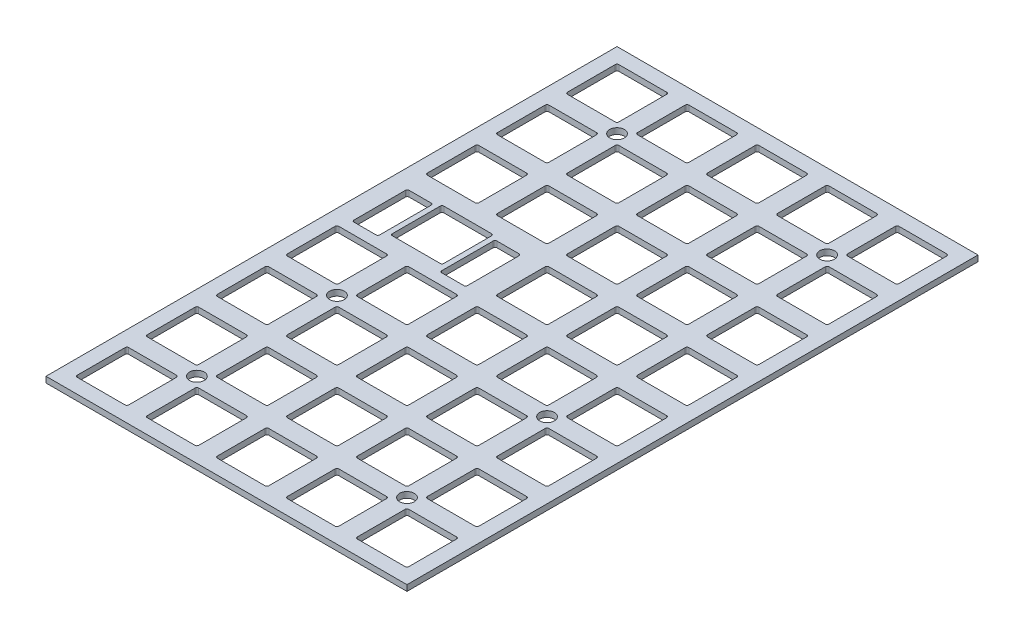
SolidWorks part; units mm, degrees
ref_plane "Front Plane" through (0, 0, 0) normal (0, 0, 1) x (1, 0, 0)
ref_plane "Top Plane" through (0, 0, 0) normal (0, 1, 0) x (1, 0, 0)
ref_plane "Right Plane" through (0, 0, 0) normal (1, 0, 0) x (0, 0, -1)
sketch "Sketch3" plane through (0, 0, 0) normal (0, 1, 0) x (1, 0, 0)
  line L0 (-104.5, -7) -> (-91.5, -7)
  line L1 (-91, -6.5) -> (-91, 6.5)
  line L2 (-91.5, 7) -> (-104.5, 7)
  line L3 (-105, 6.5) -> (-105, -6.5)
  line L4 (-85.45, -7) -> (-72.45, -7)
  line L5 (-71.95, -6.5) -> (-71.95, 6.5)
  line L6 (-72.45, 7) -> (-85.45, 7)
  line L7 (-85.95, 6.5) -> (-85.95, -6.5)
  line L8 (-66.4, -7) -> (-53.4, -7)
  line L9 (-52.9, -6.5) -> (-52.9, 6.5)
  line L10 (-53.4, 7) -> (-66.4, 7)
  line L11 (-66.9, 6.5) -> (-66.9, -6.5)
  line L12 (-47.35, -7) -> (-34.35, -7)
  line L13 (-33.85, -6.5) -> (-33.85, 6.5)
  line L14 (-34.35, 7) -> (-47.35, 7)
  line L15 (-47.85, 6.5) -> (-47.85, -6.5)
  line L16 (-28.3, -7) -> (-15.3, -7)
  line L17 (-14.8, -6.5) -> (-14.8, 6.5)
  line L18 (-15.3, 7) -> (-28.3, 7)
  line L19 (-28.8, 6.5) -> (-28.8, -6.5)
  line L20 (-104.5, -26.05) -> (-91.5, -26.05)
  line L21 (-91, -25.55) -> (-91, -12.55)
  line L22 (-91.5, -12.05) -> (-104.5, -12.05)
  line L23 (-105, -12.55) -> (-105, -25.55)
  line L24 (-85.45, -26.05) -> (-72.45, -26.05)
  line L25 (-71.95, -25.55) -> (-71.95, -12.55)
  line L26 (-72.45, -12.05) -> (-85.45, -12.05)
  line L27 (-85.95, -12.55) -> (-85.95, -25.55)
  line L28 (-66.4, -26.05) -> (-53.4, -26.05)
  line L29 (-52.9, -25.55) -> (-52.9, -12.55)
  line L30 (-53.4, -12.05) -> (-66.4, -12.05)
  line L31 (-66.9, -12.55) -> (-66.9, -25.55)
  line L32 (-47.35, -26.05) -> (-34.35, -26.05)
  line L33 (-33.85, -25.55) -> (-33.85, -12.55)
  line L34 (-34.35, -12.05) -> (-47.35, -12.05)
  line L35 (-47.85, -12.55) -> (-47.85, -25.55)
  line L36 (-28.3, -26.05) -> (-15.3, -26.05)
  line L37 (-14.8, -25.55) -> (-14.8, -12.55)
  line L38 (-15.3, -12.05) -> (-28.3, -12.05)
  line L39 (-28.8, -12.55) -> (-28.8, -25.55)
  line L40 (-104.5, -45.1) -> (-91.5, -45.1)
  line L41 (-91, -44.6) -> (-91, -31.6)
  line L42 (-91.5, -31.1) -> (-104.5, -31.1)
  line L43 (-105, -31.6) -> (-105, -44.6)
  line L44 (-85.45, -45.1) -> (-72.45, -45.1)
  line L45 (-71.95, -44.6) -> (-71.95, -31.6)
  line L46 (-72.45, -31.1) -> (-85.45, -31.1)
  line L47 (-85.95, -31.6) -> (-85.95, -44.6)
  line L48 (-66.4, -45.1) -> (-53.4, -45.1)
  line L49 (-52.9, -44.6) -> (-52.9, -31.6)
  line L50 (-53.4, -31.1) -> (-66.4, -31.1)
  line L51 (-66.9, -31.6) -> (-66.9, -44.6)
  line L52 (-47.35, -45.1) -> (-34.35, -45.1)
  line L53 (-33.85, -44.6) -> (-33.85, -31.6)
  line L54 (-34.35, -31.1) -> (-47.35, -31.1)
  line L55 (-47.85, -31.6) -> (-47.85, -44.6)
  line L56 (-28.3, -45.1) -> (-15.3, -45.1)
  line L57 (-14.8, -44.6) -> (-14.8, -31.6)
  line L58 (-15.3, -31.1) -> (-28.3, -31.1)
  line L59 (-28.8, -31.6) -> (-28.8, -44.6)
  line L60 (-94.975, -64.15) -> (-81.975, -64.15)
  line L61 (-81.475, -63.65) -> (-81.475, -50.65)
  line L62 (-81.975, -50.15) -> (-94.975, -50.15)
  line L63 (-95.475, -50.65) -> (-95.475, -63.65)
  line L64 (-66.4, -64.15) -> (-53.4, -64.15)
  line L65 (-52.9, -63.65) -> (-52.9, -50.65)
  line L66 (-53.4, -50.15) -> (-66.4, -50.15)
  line L67 (-66.9, -50.65) -> (-66.9, -63.65)
  line L68 (-47.35, -64.15) -> (-34.35, -64.15)
  line L69 (-33.85, -63.65) -> (-33.85, -50.65)
  line L70 (-34.35, -50.15) -> (-47.35, -50.15)
  line L71 (-47.85, -50.65) -> (-47.85, -63.65)
  line L72 (-28.3, -64.15) -> (-15.3, -64.15)
  line L73 (-14.8, -63.65) -> (-14.8, -50.65)
  line L74 (-15.3, -50.15) -> (-28.3, -50.15)
  line L75 (-28.8, -50.65) -> (-28.8, -63.65)
  line L76 (-104.5, -83.2) -> (-91.5, -83.2)
  line L77 (-91, -82.7) -> (-91, -69.7)
  line L78 (-91.5, -69.2) -> (-104.5, -69.2)
  line L79 (-105, -69.7) -> (-105, -82.7)
  line L80 (-85.45, -83.2) -> (-72.45, -83.2)
  line L81 (-71.95, -82.7) -> (-71.95, -69.7)
  line L82 (-72.45, -69.2) -> (-85.45, -69.2)
  line L83 (-85.95, -69.7) -> (-85.95, -82.7)
  line L84 (-66.4, -83.2) -> (-53.4, -83.2)
  line L85 (-52.9, -82.7) -> (-52.9, -69.7)
  line L86 (-53.4, -69.2) -> (-66.4, -69.2)
  line L87 (-66.9, -69.7) -> (-66.9, -82.7)
  line L88 (-47.35, -83.2) -> (-34.35, -83.2)
  line L89 (-33.85, -82.7) -> (-33.85, -69.7)
  line L90 (-34.35, -69.2) -> (-47.35, -69.2)
  line L91 (-47.85, -69.7) -> (-47.85, -82.7)
  line L92 (-28.3, -83.2) -> (-15.3, -83.2)
  line L93 (-14.8, -82.7) -> (-14.8, -69.7)
  line L94 (-15.3, -69.2) -> (-28.3, -69.2)
  line L95 (-28.8, -69.7) -> (-28.8, -82.7)
  line L96 (-104.5, -102.25) -> (-91.5, -102.25)
  line L97 (-91, -101.75) -> (-91, -88.75)
  line L98 (-91.5, -88.25) -> (-104.5, -88.25)
  line L99 (-105, -88.75) -> (-105, -101.75)
  line L100 (-85.45, -102.25) -> (-72.45, -102.25)
  line L101 (-71.95, -101.75) -> (-71.95, -88.75)
  line L102 (-72.45, -88.25) -> (-85.45, -88.25)
  line L103 (-85.95, -88.75) -> (-85.95, -101.75)
  line L104 (-66.4, -102.25) -> (-53.4, -102.25)
  line L105 (-52.9, -101.75) -> (-52.9, -88.75)
  line L106 (-53.4, -88.25) -> (-66.4, -88.25)
  line L107 (-66.9, -88.75) -> (-66.9, -101.75)
  line L108 (-47.35, -102.25) -> (-34.35, -102.25)
  line L109 (-33.85, -101.75) -> (-33.85, -88.75)
  line L110 (-34.35, -88.25) -> (-47.35, -88.25)
  line L111 (-47.85, -88.75) -> (-47.85, -101.75)
  line L112 (-28.3, -102.25) -> (-15.3, -102.25)
  line L113 (-14.8, -101.75) -> (-14.8, -88.75)
  line L114 (-15.3, -88.25) -> (-28.3, -88.25)
  line L115 (-28.8, -88.75) -> (-28.8, -101.75)
  line L116 (-104.5, -121.3) -> (-91.5, -121.3)
  line L117 (-91, -120.8) -> (-91, -107.8)
  line L118 (-91.5, -107.3) -> (-104.5, -107.3)
  line L119 (-105, -107.8) -> (-105, -120.8)
  line L120 (-85.45, -121.3) -> (-72.45, -121.3)
  line L121 (-71.95, -120.8) -> (-71.95, -107.8)
  line L122 (-72.45, -107.3) -> (-85.45, -107.3)
  line L123 (-85.95, -107.8) -> (-85.95, -120.8)
  line L124 (-66.4, -121.3) -> (-53.4, -121.3)
  line L125 (-52.9, -120.8) -> (-52.9, -107.8)
  line L126 (-53.4, -107.3) -> (-66.4, -107.3)
  line L127 (-66.9, -107.8) -> (-66.9, -120.8)
  line L128 (-47.35, -121.3) -> (-34.35, -121.3)
  line L129 (-33.85, -120.8) -> (-33.85, -107.8)
  line L130 (-34.35, -107.3) -> (-47.35, -107.3)
  line L131 (-47.85, -107.8) -> (-47.85, -120.8)
  line L132 (-28.3, -121.3) -> (-15.3, -121.3)
  line L133 (-14.8, -120.8) -> (-14.8, -107.8)
  line L134 (-15.3, -107.3) -> (-28.3, -107.3)
  line L135 (-28.8, -107.8) -> (-28.8, -120.8)
  line L136 (-104.5, -140.35) -> (-91.5, -140.35)
  line L137 (-91, -139.85) -> (-91, -126.85)
  line L138 (-91.5, -126.35) -> (-104.5, -126.35)
  line L139 (-105, -126.85) -> (-105, -139.85)
  line L140 (-85.45, -140.35) -> (-72.45, -140.35)
  line L141 (-71.95, -139.85) -> (-71.95, -126.85)
  line L142 (-72.45, -126.35) -> (-85.45, -126.35)
  line L143 (-85.95, -126.85) -> (-85.95, -139.85)
  line L144 (-66.4, -140.35) -> (-53.4, -140.35)
  line L145 (-52.9, -139.85) -> (-52.9, -126.85)
  line L146 (-53.4, -126.35) -> (-66.4, -126.35)
  line L147 (-66.9, -126.85) -> (-66.9, -139.85)
  line L148 (-47.35, -140.35) -> (-34.35, -140.35)
  line L149 (-33.85, -139.85) -> (-33.85, -126.85)
  line L150 (-34.35, -126.35) -> (-47.35, -126.35)
  line L151 (-47.85, -126.85) -> (-47.85, -139.85)
  line L152 (-28.3, -140.35) -> (-15.3, -140.35)
  line L153 (-14.8, -139.85) -> (-14.8, -126.85)
  line L154 (-15.3, -126.35) -> (-28.3, -126.35)
  line L155 (-28.8, -126.85) -> (-28.8, -139.85)
  line L156 (-103.413, -66.15) -> (-97.413, -66.15)
  line L157 (-96.913, -65.65) -> (-96.913, -51.65)
  line L158 (-97.413, -51.15) -> (-103.413, -51.15)
  line L159 (-103.913, -51.65) -> (-103.913, -65.65)
  line L160 (-79.537, -66.15) -> (-73.537, -66.15)
  line L161 (-73.037, -65.65) -> (-73.037, -51.65)
  line L162 (-73.537, -51.15) -> (-79.537, -51.15)
  line L163 (-80.037, -51.65) -> (-80.037, -65.65)
  line L165 (-109, 11) -> (-10.8, 11)
  line L166 (-109, 11) -> (-109, -144.35)
  line L167 (-109, -144.35) -> (-10.8, -144.35)
  line L168 (-10.8, 11) -> (-10.8, -144.35)
  arc A0 (-105, -6.5) -> (-104.5, -7) centre (-104.5, -6.5) ccw
  arc A1 (-91.5, -7) -> (-91, -6.5) centre (-91.5, -6.5) ccw
  arc A2 (-91, 6.5) -> (-91.5, 7) centre (-91.5, 6.5) ccw
  arc A3 (-104.5, 7) -> (-105, 6.5) centre (-104.5, 6.5) ccw
  arc A4 (-85.95, -6.5) -> (-85.45, -7) centre (-85.45, -6.5) ccw
  arc A5 (-72.45, -7) -> (-71.95, -6.5) centre (-72.45, -6.5) ccw
  arc A6 (-71.95, 6.5) -> (-72.45, 7) centre (-72.45, 6.5) ccw
  arc A7 (-85.45, 7) -> (-85.95, 6.5) centre (-85.45, 6.5) ccw
  arc A8 (-66.9, -6.5) -> (-66.4, -7) centre (-66.4, -6.5) ccw
  arc A9 (-53.4, -7) -> (-52.9, -6.5) centre (-53.4, -6.5) ccw
  arc A10 (-52.9, 6.5) -> (-53.4, 7) centre (-53.4, 6.5) ccw
  arc A11 (-66.4, 7) -> (-66.9, 6.5) centre (-66.4, 6.5) ccw
  arc A12 (-47.85, -6.5) -> (-47.35, -7) centre (-47.35, -6.5) ccw
  arc A13 (-34.35, -7) -> (-33.85, -6.5) centre (-34.35, -6.5) ccw
  arc A14 (-33.85, 6.5) -> (-34.35, 7) centre (-34.35, 6.5) ccw
  arc A15 (-47.35, 7) -> (-47.85, 6.5) centre (-47.35, 6.5) ccw
  arc A16 (-28.8, -6.5) -> (-28.3, -7) centre (-28.3, -6.5) ccw
  arc A17 (-15.3, -7) -> (-14.8, -6.5) centre (-15.3, -6.5) ccw
  arc A18 (-14.8, 6.5) -> (-15.3, 7) centre (-15.3, 6.5) ccw
  arc A19 (-28.3, 7) -> (-28.8, 6.5) centre (-28.3, 6.5) ccw
  arc A20 (-105, -25.55) -> (-104.5, -26.05) centre (-104.5, -25.55) ccw
  arc A21 (-91.5, -26.05) -> (-91, -25.55) centre (-91.5, -25.55) ccw
  arc A22 (-91, -12.55) -> (-91.5, -12.05) centre (-91.5, -12.55) ccw
  arc A23 (-104.5, -12.05) -> (-105, -12.55) centre (-104.5, -12.55) ccw
  arc A24 (-85.95, -25.55) -> (-85.45, -26.05) centre (-85.45, -25.55) ccw
  arc A25 (-72.45, -26.05) -> (-71.95, -25.55) centre (-72.45, -25.55) ccw
  arc A26 (-71.95, -12.55) -> (-72.45, -12.05) centre (-72.45, -12.55) ccw
  arc A27 (-85.45, -12.05) -> (-85.95, -12.55) centre (-85.45, -12.55) ccw
  arc A28 (-66.9, -25.55) -> (-66.4, -26.05) centre (-66.4, -25.55) ccw
  arc A29 (-53.4, -26.05) -> (-52.9, -25.55) centre (-53.4, -25.55) ccw
  arc A30 (-52.9, -12.55) -> (-53.4, -12.05) centre (-53.4, -12.55) ccw
  arc A31 (-66.4, -12.05) -> (-66.9, -12.55) centre (-66.4, -12.55) ccw
  arc A32 (-47.85, -25.55) -> (-47.35, -26.05) centre (-47.35, -25.55) ccw
  arc A33 (-34.35, -26.05) -> (-33.85, -25.55) centre (-34.35, -25.55) ccw
  arc A34 (-33.85, -12.55) -> (-34.35, -12.05) centre (-34.35, -12.55) ccw
  arc A35 (-47.35, -12.05) -> (-47.85, -12.55) centre (-47.35, -12.55) ccw
  arc A36 (-28.8, -25.55) -> (-28.3, -26.05) centre (-28.3, -25.55) ccw
  arc A37 (-15.3, -26.05) -> (-14.8, -25.55) centre (-15.3, -25.55) ccw
  arc A38 (-14.8, -12.55) -> (-15.3, -12.05) centre (-15.3, -12.55) ccw
  arc A39 (-28.3, -12.05) -> (-28.8, -12.55) centre (-28.3, -12.55) ccw
  arc A40 (-105, -44.6) -> (-104.5, -45.1) centre (-104.5, -44.6) ccw
  arc A41 (-91.5, -45.1) -> (-91, -44.6) centre (-91.5, -44.6) ccw
  arc A42 (-91, -31.6) -> (-91.5, -31.1) centre (-91.5, -31.6) ccw
  arc A43 (-104.5, -31.1) -> (-105, -31.6) centre (-104.5, -31.6) ccw
  arc A44 (-85.95, -44.6) -> (-85.45, -45.1) centre (-85.45, -44.6) ccw
  arc A45 (-72.45, -45.1) -> (-71.95, -44.6) centre (-72.45, -44.6) ccw
  arc A46 (-71.95, -31.6) -> (-72.45, -31.1) centre (-72.45, -31.6) ccw
  arc A47 (-85.45, -31.1) -> (-85.95, -31.6) centre (-85.45, -31.6) ccw
  arc A48 (-66.9, -44.6) -> (-66.4, -45.1) centre (-66.4, -44.6) ccw
  arc A49 (-53.4, -45.1) -> (-52.9, -44.6) centre (-53.4, -44.6) ccw
  arc A50 (-52.9, -31.6) -> (-53.4, -31.1) centre (-53.4, -31.6) ccw
  arc A51 (-66.4, -31.1) -> (-66.9, -31.6) centre (-66.4, -31.6) ccw
  arc A52 (-47.85, -44.6) -> (-47.35, -45.1) centre (-47.35, -44.6) ccw
  arc A53 (-34.35, -45.1) -> (-33.85, -44.6) centre (-34.35, -44.6) ccw
  arc A54 (-33.85, -31.6) -> (-34.35, -31.1) centre (-34.35, -31.6) ccw
  arc A55 (-47.35, -31.1) -> (-47.85, -31.6) centre (-47.35, -31.6) ccw
  arc A56 (-28.8, -44.6) -> (-28.3, -45.1) centre (-28.3, -44.6) ccw
  arc A57 (-15.3, -45.1) -> (-14.8, -44.6) centre (-15.3, -44.6) ccw
  arc A58 (-14.8, -31.6) -> (-15.3, -31.1) centre (-15.3, -31.6) ccw
  arc A59 (-28.3, -31.1) -> (-28.8, -31.6) centre (-28.3, -31.6) ccw
  arc A60 (-95.475, -63.65) -> (-94.975, -64.15) centre (-94.975, -63.65) ccw
  arc A61 (-81.975, -64.15) -> (-81.475, -63.65) centre (-81.975, -63.65) ccw
  arc A62 (-81.475, -50.65) -> (-81.975, -50.15) centre (-81.975, -50.65) ccw
  arc A63 (-94.975, -50.15) -> (-95.475, -50.65) centre (-94.975, -50.65) ccw
  arc A64 (-66.9, -63.65) -> (-66.4, -64.15) centre (-66.4, -63.65) ccw
  arc A65 (-53.4, -64.15) -> (-52.9, -63.65) centre (-53.4, -63.65) ccw
  arc A66 (-52.9, -50.65) -> (-53.4, -50.15) centre (-53.4, -50.65) ccw
  arc A67 (-66.4, -50.15) -> (-66.9, -50.65) centre (-66.4, -50.65) ccw
  arc A68 (-47.85, -63.65) -> (-47.35, -64.15) centre (-47.35, -63.65) ccw
  arc A69 (-34.35, -64.15) -> (-33.85, -63.65) centre (-34.35, -63.65) ccw
  arc A70 (-33.85, -50.65) -> (-34.35, -50.15) centre (-34.35, -50.65) ccw
  arc A71 (-47.35, -50.15) -> (-47.85, -50.65) centre (-47.35, -50.65) ccw
  arc A72 (-28.8, -63.65) -> (-28.3, -64.15) centre (-28.3, -63.65) ccw
  arc A73 (-15.3, -64.15) -> (-14.8, -63.65) centre (-15.3, -63.65) ccw
  arc A74 (-14.8, -50.65) -> (-15.3, -50.15) centre (-15.3, -50.65) ccw
  arc A75 (-28.3, -50.15) -> (-28.8, -50.65) centre (-28.3, -50.65) ccw
  arc A76 (-105, -82.7) -> (-104.5, -83.2) centre (-104.5, -82.7) ccw
  arc A77 (-91.5, -83.2) -> (-91, -82.7) centre (-91.5, -82.7) ccw
  arc A78 (-91, -69.7) -> (-91.5, -69.2) centre (-91.5, -69.7) ccw
  arc A79 (-104.5, -69.2) -> (-105, -69.7) centre (-104.5, -69.7) ccw
  arc A80 (-85.95, -82.7) -> (-85.45, -83.2) centre (-85.45, -82.7) ccw
  arc A81 (-72.45, -83.2) -> (-71.95, -82.7) centre (-72.45, -82.7) ccw
  arc A82 (-71.95, -69.7) -> (-72.45, -69.2) centre (-72.45, -69.7) ccw
  arc A83 (-85.45, -69.2) -> (-85.95, -69.7) centre (-85.45, -69.7) ccw
  arc A84 (-66.9, -82.7) -> (-66.4, -83.2) centre (-66.4, -82.7) ccw
  arc A85 (-53.4, -83.2) -> (-52.9, -82.7) centre (-53.4, -82.7) ccw
  arc A86 (-52.9, -69.7) -> (-53.4, -69.2) centre (-53.4, -69.7) ccw
  arc A87 (-66.4, -69.2) -> (-66.9, -69.7) centre (-66.4, -69.7) ccw
  arc A88 (-47.85, -82.7) -> (-47.35, -83.2) centre (-47.35, -82.7) ccw
  arc A89 (-34.35, -83.2) -> (-33.85, -82.7) centre (-34.35, -82.7) ccw
  arc A90 (-33.85, -69.7) -> (-34.35, -69.2) centre (-34.35, -69.7) ccw
  arc A91 (-47.35, -69.2) -> (-47.85, -69.7) centre (-47.35, -69.7) ccw
  arc A92 (-28.8, -82.7) -> (-28.3, -83.2) centre (-28.3, -82.7) ccw
  arc A93 (-15.3, -83.2) -> (-14.8, -82.7) centre (-15.3, -82.7) ccw
  arc A94 (-14.8, -69.7) -> (-15.3, -69.2) centre (-15.3, -69.7) ccw
  arc A95 (-28.3, -69.2) -> (-28.8, -69.7) centre (-28.3, -69.7) ccw
  arc A96 (-105, -101.75) -> (-104.5, -102.25) centre (-104.5, -101.75) ccw
  arc A97 (-91.5, -102.25) -> (-91, -101.75) centre (-91.5, -101.75) ccw
  arc A98 (-91, -88.75) -> (-91.5, -88.25) centre (-91.5, -88.75) ccw
  arc A99 (-104.5, -88.25) -> (-105, -88.75) centre (-104.5, -88.75) ccw
  arc A100 (-85.95, -101.75) -> (-85.45, -102.25) centre (-85.45, -101.75) ccw
  arc A101 (-72.45, -102.25) -> (-71.95, -101.75) centre (-72.45, -101.75) ccw
  arc A102 (-71.95, -88.75) -> (-72.45, -88.25) centre (-72.45, -88.75) ccw
  arc A103 (-85.45, -88.25) -> (-85.95, -88.75) centre (-85.45, -88.75) ccw
  arc A104 (-66.9, -101.75) -> (-66.4, -102.25) centre (-66.4, -101.75) ccw
  arc A105 (-53.4, -102.25) -> (-52.9, -101.75) centre (-53.4, -101.75) ccw
  arc A106 (-52.9, -88.75) -> (-53.4, -88.25) centre (-53.4, -88.75) ccw
  arc A107 (-66.4, -88.25) -> (-66.9, -88.75) centre (-66.4, -88.75) ccw
  arc A108 (-47.85, -101.75) -> (-47.35, -102.25) centre (-47.35, -101.75) ccw
  arc A109 (-34.35, -102.25) -> (-33.85, -101.75) centre (-34.35, -101.75) ccw
  arc A110 (-33.85, -88.75) -> (-34.35, -88.25) centre (-34.35, -88.75) ccw
  arc A111 (-47.35, -88.25) -> (-47.85, -88.75) centre (-47.35, -88.75) ccw
  arc A112 (-28.8, -101.75) -> (-28.3, -102.25) centre (-28.3, -101.75) ccw
  arc A113 (-15.3, -102.25) -> (-14.8, -101.75) centre (-15.3, -101.75) ccw
  arc A114 (-14.8, -88.75) -> (-15.3, -88.25) centre (-15.3, -88.75) ccw
  arc A115 (-28.3, -88.25) -> (-28.8, -88.75) centre (-28.3, -88.75) ccw
  arc A116 (-105, -120.8) -> (-104.5, -121.3) centre (-104.5, -120.8) ccw
  arc A117 (-91.5, -121.3) -> (-91, -120.8) centre (-91.5, -120.8) ccw
  arc A118 (-91, -107.8) -> (-91.5, -107.3) centre (-91.5, -107.8) ccw
  arc A119 (-104.5, -107.3) -> (-105, -107.8) centre (-104.5, -107.8) ccw
  arc A120 (-85.95, -120.8) -> (-85.45, -121.3) centre (-85.45, -120.8) ccw
  arc A121 (-72.45, -121.3) -> (-71.95, -120.8) centre (-72.45, -120.8) ccw
  arc A122 (-71.95, -107.8) -> (-72.45, -107.3) centre (-72.45, -107.8) ccw
  arc A123 (-85.45, -107.3) -> (-85.95, -107.8) centre (-85.45, -107.8) ccw
  arc A124 (-66.9, -120.8) -> (-66.4, -121.3) centre (-66.4, -120.8) ccw
  arc A125 (-53.4, -121.3) -> (-52.9, -120.8) centre (-53.4, -120.8) ccw
  arc A126 (-52.9, -107.8) -> (-53.4, -107.3) centre (-53.4, -107.8) ccw
  arc A127 (-66.4, -107.3) -> (-66.9, -107.8) centre (-66.4, -107.8) ccw
  arc A128 (-47.85, -120.8) -> (-47.35, -121.3) centre (-47.35, -120.8) ccw
  arc A129 (-34.35, -121.3) -> (-33.85, -120.8) centre (-34.35, -120.8) ccw
  arc A130 (-33.85, -107.8) -> (-34.35, -107.3) centre (-34.35, -107.8) ccw
  arc A131 (-47.35, -107.3) -> (-47.85, -107.8) centre (-47.35, -107.8) ccw
  arc A132 (-28.8, -120.8) -> (-28.3, -121.3) centre (-28.3, -120.8) ccw
  arc A133 (-15.3, -121.3) -> (-14.8, -120.8) centre (-15.3, -120.8) ccw
  arc A134 (-14.8, -107.8) -> (-15.3, -107.3) centre (-15.3, -107.8) ccw
  arc A135 (-28.3, -107.3) -> (-28.8, -107.8) centre (-28.3, -107.8) ccw
  arc A136 (-105, -139.85) -> (-104.5, -140.35) centre (-104.5, -139.85) ccw
  arc A137 (-91.5, -140.35) -> (-91, -139.85) centre (-91.5, -139.85) ccw
  arc A138 (-91, -126.85) -> (-91.5, -126.35) centre (-91.5, -126.85) ccw
  arc A139 (-104.5, -126.35) -> (-105, -126.85) centre (-104.5, -126.85) ccw
  arc A140 (-85.95, -139.85) -> (-85.45, -140.35) centre (-85.45, -139.85) ccw
  arc A141 (-72.45, -140.35) -> (-71.95, -139.85) centre (-72.45, -139.85) ccw
  arc A142 (-71.95, -126.85) -> (-72.45, -126.35) centre (-72.45, -126.85) ccw
  arc A143 (-85.45, -126.35) -> (-85.95, -126.85) centre (-85.45, -126.85) ccw
  arc A144 (-66.9, -139.85) -> (-66.4, -140.35) centre (-66.4, -139.85) ccw
  arc A145 (-53.4, -140.35) -> (-52.9, -139.85) centre (-53.4, -139.85) ccw
  arc A146 (-52.9, -126.85) -> (-53.4, -126.35) centre (-53.4, -126.85) ccw
  arc A147 (-66.4, -126.35) -> (-66.9, -126.85) centre (-66.4, -126.85) ccw
  arc A148 (-47.85, -139.85) -> (-47.35, -140.35) centre (-47.35, -139.85) ccw
  arc A149 (-34.35, -140.35) -> (-33.85, -139.85) centre (-34.35, -139.85) ccw
  arc A150 (-33.85, -126.85) -> (-34.35, -126.35) centre (-34.35, -126.85) ccw
  arc A151 (-47.35, -126.35) -> (-47.85, -126.85) centre (-47.35, -126.85) ccw
  arc A152 (-28.8, -139.85) -> (-28.3, -140.35) centre (-28.3, -139.85) ccw
  arc A153 (-15.3, -140.35) -> (-14.8, -139.85) centre (-15.3, -139.85) ccw
  arc A154 (-14.8, -126.85) -> (-15.3, -126.35) centre (-15.3, -126.85) ccw
  arc A155 (-28.3, -126.35) -> (-28.8, -126.85) centre (-28.3, -126.85) ccw
  arc A156 (-103.913, -65.65) -> (-103.413, -66.15) centre (-103.413, -65.65) ccw
  arc A157 (-97.413, -66.15) -> (-96.913, -65.65) centre (-97.413, -65.65) ccw
  arc A158 (-96.913, -51.65) -> (-97.413, -51.15) centre (-97.413, -51.65) ccw
  arc A159 (-103.413, -51.15) -> (-103.913, -51.65) centre (-103.413, -51.65) ccw
  arc A160 (-80.037, -65.65) -> (-79.537, -66.15) centre (-79.537, -65.65) ccw
  arc A161 (-73.537, -66.15) -> (-73.037, -65.65) centre (-73.537, -65.65) ccw
  arc A162 (-73.037, -51.65) -> (-73.537, -51.15) centre (-73.537, -51.65) ccw
  arc A163 (-79.537, -51.15) -> (-80.037, -51.65) centre (-79.537, -51.65) ccw
  dimension "D1" = 4
  dimension "D2" = 4
  dimension "D3" = 4
  dimension "D4" = 4
  dimension "D5" = 98.2
extrude "Boss-Extrude2" add sketch "Sketch3" along normal blind 1.6 separate body
sketch "Sketch4" plane through (0, 1.6, 0) normal (0, 1, 0) x (1, 0, 0)
  line L0 (-10.8, -144.35) -> (-10.8, 11) construction
  line L1 (-104.5, -7) -> (-104.5, -12.05) construction
  line L2 (-104.5, -83.2) -> (-104.5, -88.25) construction
  line L3 (-104.5, -121.3) -> (-104.5, -126.35) construction
  line L4 (-91, 6.5) -> (-85.95, 6.5) construction
  line L5 (-33.85, 6.5) -> (-28.8, 6.5) construction
  circle A0 centre (-88.475, -9.525) radius 2
  circle A1 centre (-31.325, -9.525) radius 2
  circle A2 centre (-88.475, -85.725) radius 2
  circle A3 centre (-31.325, -85.725) radius 2
  circle A4 centre (-88.475, -123.825) radius 2
  circle A5 centre (-31.325, -123.825) radius 2
  point P28 (-104.5, -123.825)
  point P29 (-104.5, -85.725)
  point P30 (-104.5, -9.525)
  point P39 (-31.325, 6.5)
  point P40 (-88.475, 6.5)
  point P41 (0, 0)
  point P42 (0, 0)
  point P43 (0, 0)
  point P44 (0, 0)
  point P45 (0, 0)
  point P46 (0, 0)
  point P47 (0, 0)
  dimension "D2" = 4
  dimension "D1" = 98.2
extrude "Cut-Extrude2" cut sketch "Sketch4" against normal through all
equation "\"d\"=4"
